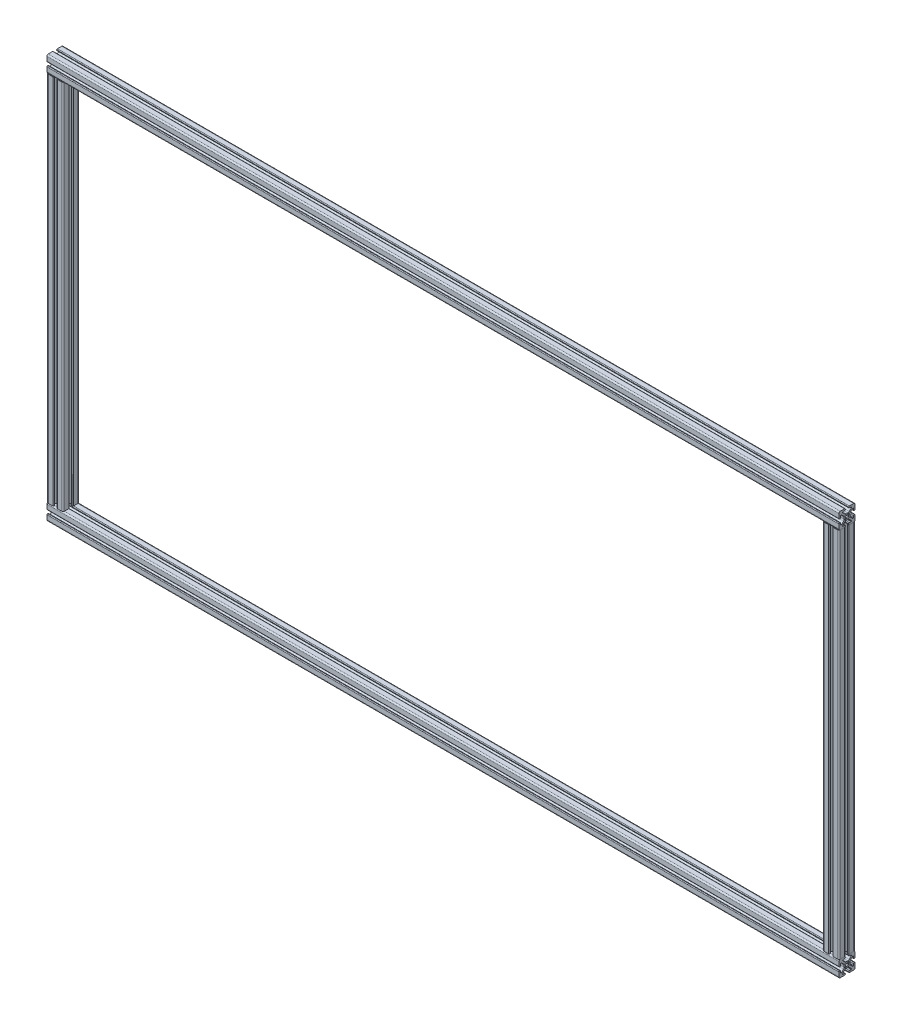
SolidWorks part; units mm, degrees
material "6061 Alloy"
ref_plane "Front Plane" through (0, 0, 0) normal (0, 0, 1) x (1, 0, 0)
ref_plane "Top Plane" through (0, 0, 0) normal (0, 1, 0) x (1, 0, 0)
ref_plane "Right Plane" through (0, 0, 0) normal (1, 0, 0) x (0, 0, -1)
sketch3d "glassFrame"
  line L1 (-914.4, -457.2, 0) -> (914.4, -457.2, 0)
  line L2 (-914.4, -457.2, 0) -> (-914.4, 457.2, 0)
  line L3 (-914.4, 457.2, 0) -> (914.4, 457.2, 0)
  line L4 (914.4, -457.2, 0) -> (914.4, 457.2, 0)
  line L5 (-914.4, -457.2, 0) -> (914.4, 457.2, 0) construction
  line L6 (-914.4, 457.2, 0) -> (914.4, -457.2, 0) construction
  point P0 (0, 0, 0)
  dimension "D1" = 1828.8
  dimension "D2" = 914.4
other "15 series 1515-S-BLACK(1)"
ref_plane "Plane1" through (-914.4, 457.2, 0) normal (1, 0, 0) x (0, 0, -1)
sketch "Sketch1" plane through (-914.4, 457.2, 0) normal (1, 0, 0) x (0, 0, -1)
  line L0 (-3.0179, 1.4014) -> (-4.3388, 2.7224)
  line L1 (-2.7224, 4.3388) -> (-1.4014, 3.0179)
  line L2 (1.4014, 3.0179) -> (2.7224, 4.3388)
  line L3 (4.3388, 2.7224) -> (3.0179, 1.4014)
  line L4 (3.0179, -1.4014) -> (4.3388, -2.7224)
  line L5 (2.7224, -4.3388) -> (1.4014, -3.0179)
  line L6 (-1.4014, -3.0179) -> (-2.7224, -4.3388)
  line L7 (-4.3388, -2.7224) -> (-3.0179, -1.4014)
  line L8 (-14.986, -9.398) -> (-14.986, -5.6388)
  line L9 (-16.5608, -4.064) -> (-17.4752, -4.064)
  line L10 (-19.05, -5.6388) -> (-19.05, -15.875)
  line L11 (-15.875, -19.05) -> (-5.6388, -19.05)
  line L12 (-4.064, -17.4752) -> (-4.064, -16.5608)
  line L13 (-5.6388, -14.986) -> (-9.398, -14.986)
  line L14 (-10.287, -14.097) -> (-10.287, -13.5289)
  line L15 (-10.0266, -12.9003) -> (-5.2555, -8.1292)
  line L16 (-1.8969, -6.738) -> (1.8969, -6.738)
  line L17 (5.2555, -8.1292) -> (10.0266, -12.9003)
  line L18 (10.287, -13.5289) -> (10.287, -14.097)
  line L19 (9.398, -14.986) -> (5.6388, -14.986)
  line L20 (4.064, -16.5608) -> (4.064, -17.4752)
  line L21 (5.6388, -19.05) -> (15.875, -19.05)
  line L22 (19.05, -15.875) -> (19.05, -5.6388)
  line L23 (17.4752, -4.064) -> (16.5608, -4.064)
  line L24 (14.986, -5.6388) -> (14.986, -9.398)
  line L25 (14.097, -10.287) -> (13.5289, -10.287)
  line L26 (12.9003, -10.0266) -> (8.1292, -5.2555)
  line L27 (6.738, -1.8969) -> (6.738, 1.8969)
  line L28 (8.1292, 5.2555) -> (12.9003, 10.0266)
  line L29 (13.5289, 10.287) -> (14.097, 10.287)
  line L30 (14.986, 9.398) -> (14.986, 5.6388)
  line L31 (16.5608, 4.064) -> (17.4752, 4.064)
  line L32 (19.05, 5.6388) -> (19.05, 15.875)
  line L33 (15.875, 19.05) -> (5.6388, 19.05)
  line L34 (4.064, 17.4752) -> (4.064, 16.5608)
  line L35 (5.6388, 14.986) -> (9.398, 14.986)
  line L36 (10.287, 14.097) -> (10.287, 13.5289)
  line L37 (10.0266, 12.9003) -> (5.2555, 8.1292)
  line L38 (1.8969, 6.738) -> (-1.8969, 6.738)
  line L39 (-5.2555, 8.1292) -> (-10.0266, 12.9003)
  line L40 (-10.287, 13.5289) -> (-10.287, 14.097)
  line L41 (-9.398, 14.986) -> (-5.6388, 14.986)
  line L42 (-4.064, 16.5608) -> (-4.064, 17.4752)
  line L43 (-5.6388, 19.05) -> (-15.875, 19.05)
  line L44 (-19.05, 15.875) -> (-19.05, 5.6388)
  line L45 (-17.4752, 4.064) -> (-16.5608, 4.064)
  line L46 (-14.986, 5.6388) -> (-14.986, 9.398)
  line L47 (-14.097, 10.287) -> (-13.5289, 10.287)
  line L48 (-12.9003, 10.0266) -> (-8.1292, 5.2555)
  line L49 (-6.738, 1.8969) -> (-6.738, -1.8969)
  line L50 (-8.1292, -5.2555) -> (-12.9003, -10.0266)
  line L51 (-13.5289, -10.287) -> (-14.097, -10.287)
  arc A0 (-3.0179, 1.4014) -> (-3.0179, -1.4014) centre (0, 0) ccw
  arc A1 (-2.7224, 4.3388) -> (-4.3388, 2.7224) centre (-3.5306, 3.5306) ccw
  arc A2 (1.4014, 3.0179) -> (-1.4014, 3.0179) centre (0, 0) ccw
  arc A3 (4.3388, 2.7224) -> (2.7224, 4.3388) centre (3.5306, 3.5306) ccw
  arc A4 (3.0179, -1.4014) -> (3.0179, 1.4014) centre (0, 0) ccw
  arc A5 (2.7224, -4.3388) -> (4.3388, -2.7224) centre (3.5306, -3.5306) ccw
  arc A6 (-1.4014, -3.0179) -> (1.4014, -3.0179) centre (0, 0) ccw
  arc A7 (-4.3388, -2.7224) -> (-2.7224, -4.3388) centre (-3.5306, -3.5306) ccw
  arc A8 (-14.986, -9.398) -> (-14.097, -10.287) centre (-14.097, -9.398) ccw
  arc A9 (-14.986, -5.6388) -> (-16.5608, -4.064) centre (-16.5608, -5.6388) ccw
  arc A10 (-17.4752, -4.064) -> (-19.05, -5.6388) centre (-17.4752, -5.6388) ccw
  arc A11 (-19.05, -15.875) -> (-15.875, -19.05) centre (-15.875, -15.875) ccw
  arc A12 (-5.6388, -19.05) -> (-4.064, -17.4752) centre (-5.6388, -17.4752) ccw
  arc A13 (-4.064, -16.5608) -> (-5.6388, -14.986) centre (-5.6388, -16.5608) ccw
  arc A14 (-10.287, -14.097) -> (-9.398, -14.986) centre (-9.398, -14.097) ccw
  arc A15 (-10.0266, -12.9003) -> (-10.287, -13.5289) centre (-9.398, -13.5289) ccw
  arc A16 (-1.8969, -6.738) -> (-5.2555, -8.1292) centre (-1.8969, -11.4878) ccw
  arc A17 (5.2555, -8.1292) -> (1.8969, -6.738) centre (1.8969, -11.4878) ccw
  arc A18 (10.287, -13.5289) -> (10.0266, -12.9003) centre (9.398, -13.5289) ccw
  arc A19 (9.398, -14.986) -> (10.287, -14.097) centre (9.398, -14.097) ccw
  arc A20 (5.6388, -14.986) -> (4.064, -16.5608) centre (5.6388, -16.5608) ccw
  arc A21 (4.064, -17.4752) -> (5.6388, -19.05) centre (5.6388, -17.4752) ccw
  arc A22 (15.875, -19.05) -> (19.05, -15.875) centre (15.875, -15.875) ccw
  arc A23 (19.05, -5.6388) -> (17.4752, -4.064) centre (17.4752, -5.6388) ccw
  arc A24 (16.5608, -4.064) -> (14.986, -5.6388) centre (16.5608, -5.6388) ccw
  arc A25 (14.097, -10.287) -> (14.986, -9.398) centre (14.097, -9.398) ccw
  arc A26 (12.9003, -10.0266) -> (13.5289, -10.287) centre (13.5289, -9.398) ccw
  arc A27 (6.738, -1.8969) -> (8.1292, -5.2555) centre (11.4878, -1.8969) ccw
  arc A28 (8.1292, 5.2555) -> (6.738, 1.8969) centre (11.4878, 1.8969) ccw
  arc A29 (13.5289, 10.287) -> (12.9003, 10.0266) centre (13.5289, 9.398) ccw
  arc A30 (14.986, 9.398) -> (14.097, 10.287) centre (14.097, 9.398) ccw
  arc A31 (14.986, 5.6388) -> (16.5608, 4.064) centre (16.5608, 5.6388) ccw
  arc A32 (17.4752, 4.064) -> (19.05, 5.6388) centre (17.4752, 5.6388) ccw
  arc A33 (19.05, 15.875) -> (15.875, 19.05) centre (15.875, 15.875) ccw
  arc A34 (5.6388, 19.05) -> (4.064, 17.4752) centre (5.6388, 17.4752) ccw
  arc A35 (4.064, 16.5608) -> (5.6388, 14.986) centre (5.6388, 16.5608) ccw
  arc A36 (10.287, 14.097) -> (9.398, 14.986) centre (9.398, 14.097) ccw
  arc A37 (10.0266, 12.9003) -> (10.287, 13.5289) centre (9.398, 13.5289) ccw
  arc A38 (1.8969, 6.738) -> (5.2555, 8.1292) centre (1.8969, 11.4878) ccw
  arc A39 (-5.2555, 8.1292) -> (-1.8969, 6.738) centre (-1.8969, 11.4878) ccw
  arc A40 (-10.287, 13.5289) -> (-10.0266, 12.9003) centre (-9.398, 13.5289) ccw
  arc A41 (-9.398, 14.986) -> (-10.287, 14.097) centre (-9.398, 14.097) ccw
  arc A42 (-5.6388, 14.986) -> (-4.064, 16.5608) centre (-5.6388, 16.5608) ccw
  arc A43 (-4.064, 17.4752) -> (-5.6388, 19.05) centre (-5.6388, 17.4752) ccw
  arc A44 (-15.875, 19.05) -> (-19.05, 15.875) centre (-15.875, 15.875) ccw
  arc A45 (-19.05, 5.6388) -> (-17.4752, 4.064) centre (-17.4752, 5.6388) ccw
  arc A46 (-16.5608, 4.064) -> (-14.986, 5.6388) centre (-16.5608, 5.6388) ccw
  arc A47 (-14.097, 10.287) -> (-14.986, 9.398) centre (-14.097, 9.398) ccw
  arc A48 (-12.9003, 10.0266) -> (-13.5289, 10.287) centre (-13.5289, 9.398) ccw
  arc A49 (-6.738, 1.8969) -> (-8.1292, 5.2555) centre (-11.4878, 1.8969) ccw
  arc A50 (-8.1292, -5.2555) -> (-6.738, -1.8969) centre (-11.4878, -1.8969) ccw
  arc A51 (-13.5289, -10.287) -> (-12.9003, -10.0266) centre (-13.5289, -9.398) ccw
  point P0 (0, 0)
